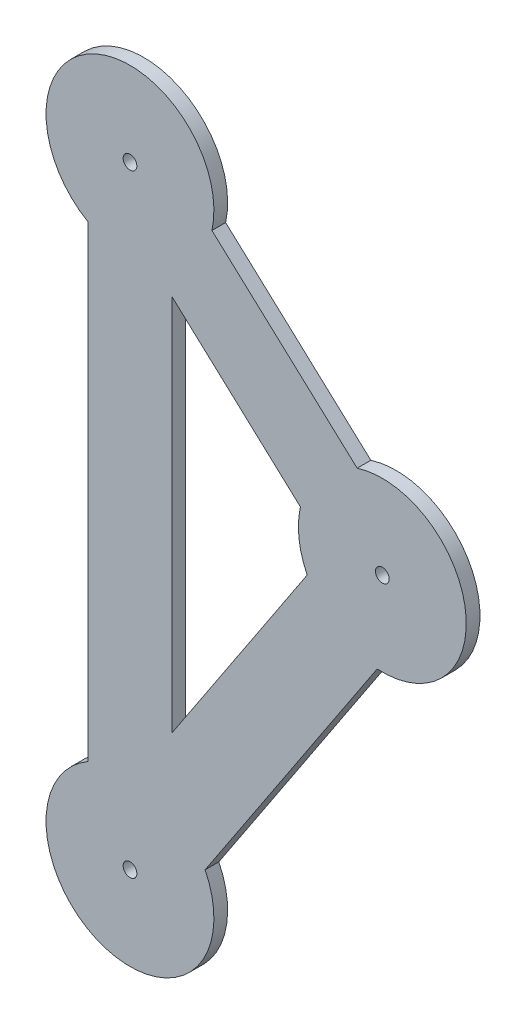
SolidWorks part; units mm, degrees
ref_plane "Front Plane" through (0, 0, 0) normal (0, 0, 1) x (1, 0, 0)
ref_plane "Top Plane" through (0, 0, 0) normal (0, 1, 0) x (1, 0, 0)
ref_plane "Right Plane" through (0, 0, 0) normal (1, 0, 0) x (0, 0, -1)
sketch "Sketch1" plane through (0, 0, 0) normal (0, 0, 1) x (1, 0, 0)
  line L0 (19.05, 0) -> (133.5945, 173.0413) construction
  line L1 (0, 0) -> (38.1, 0)
  line L2 (0, 0) -> (0, 278.13)
  line L3 (0, 278.13) -> (38.1, 278.13)
  line L4 (38.1, 0) -> (38.1, 278.13)
  line L5 (133.5945, 173.0413) -> (19.05, 278.13) construction
  line L6 (16.0228, 306.76) -> (158.4552, 176.0856)
  line L7 (158.4552, 176.0856) -> (-3.2854, -68.2544)
  line L8 (29.1885, 242.9757) -> (108.7338, 169.997)
  line L9 (108.7338, 169.997) -> (30.8659, 52.3627)
  circle A0 centre (19.05, 278.13) radius 3.1115
  circle A1 centre (19.05, 0) radius 3.1115
  circle A2 centre (133.5945, 173.0413) radius 3.1115
  circle A3 centre (19.05, 278.13) radius 38.1
  circle A4 centre (133.5945, 173.0413) radius 38.1
  circle A5 centre (19.05, 0) radius 38.1
  dimension "D3" = 155.448
  dimension "D5" = 6.223
  dimension "D10" = 76.2
  dimension "D11" = 76.2
  dimension "D12" = 76.2
  dimension "D1" = 278.13
  dimension "D2" = 38.1
  dimension "D4" = 207.518
  dimension "D6" = 19.05
  dimension "D7" = 19.05
  dimension "D8" = 38.1
  dimension "D9" = 19.05
extrude "Boss-Extrude1" add sketch "Sketch1" along normal blind 6.223
